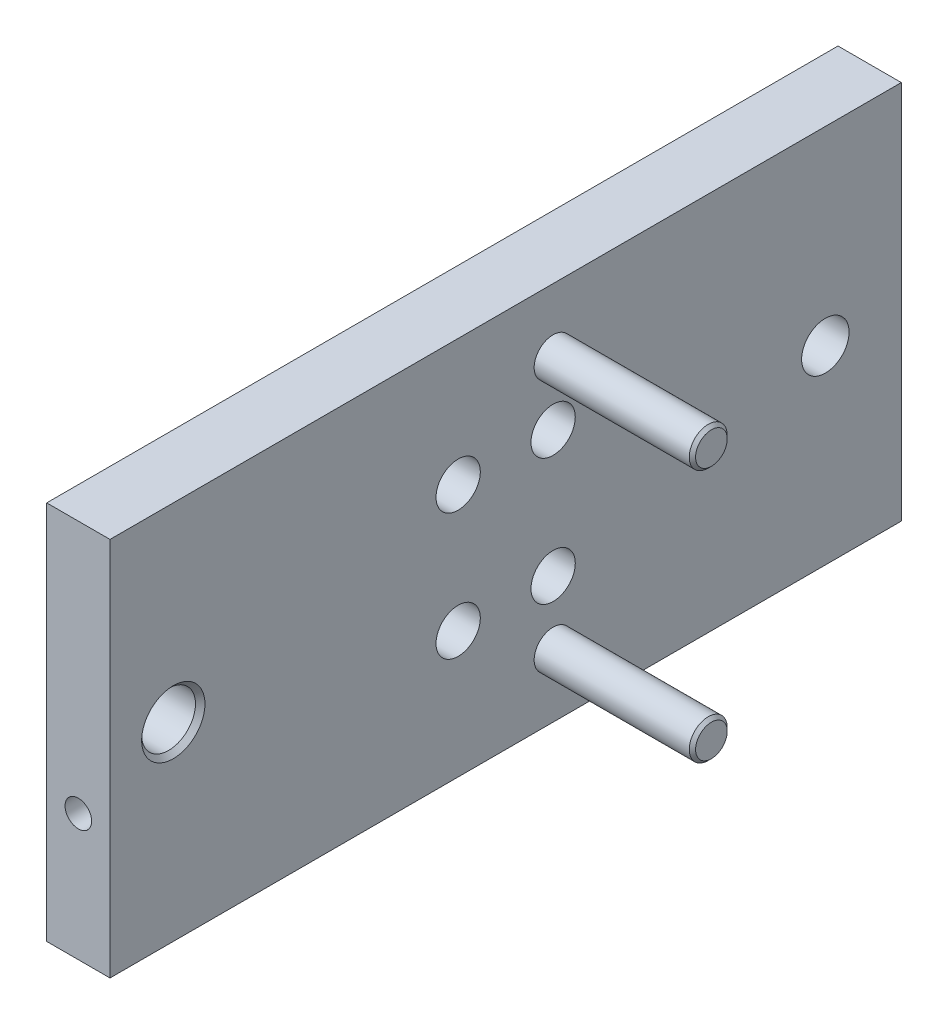
SolidWorks part; units mm, degrees
ref_plane "Front" through (0, 0, 0) normal (0, 0, 1) x (1, 0, 0)
ref_plane "Top" through (0, 0, 0) normal (0, 1, 0) x (1, 0, 0)
ref_plane "Right" through (0, 0, 0) normal (1, 0, 0) x (0, 0, -1)
sketch "Sketch1" plane through (0, 0, 0) normal (1, 0, 0) x (0, 0, -1)
  line L1 (0, 0) -> (-125, 0)
  line L2 (0, 0) -> (0, 60)
  line L3 (0, 60) -> (-125, 60)
  line L4 (-125, 0) -> (-125, 60)
  dimension "D1" = 60
  dimension "D2" = 125
extrude "Boss-Extrude1" add sketch "Sketch1" along normal blind 10
sketch "Sketch12" plane through (10, 0, 0) normal (1, 0, 0) x (0, 0, -1)
  line L0 (0, 30) -> (-125, 30) construction
  line L1 (0, 0) -> (0, 60) construction
  line L2 (-125, 60) -> (-125, 0) construction
  circle A0 centre (-55, 10) radius 3
  circle A1 centre (-55, 50) radius 3
  dimension "D1" = 6
  dimension "D2" = 55
  dimension "D3" = 40
extrude "Boss-Extrude2" add sketch "Sketch12" along normal blind 25
cosmetic thread "Cosmetic Thread3" parameters "D1"=10, "D2"=4.891
cosmetic thread "Cosmetic Thread4" parameters "D1"=10, "D2"=4.891
hole_wizard "M10 Tapped Hole1" positions "Sketch6" profile "Sketch5" tap size "M10" standard "ISO"
sketch "Sketch6" plane through (10, 0, 0) normal (1, 0, 0) x (0, 0, -1)
  line L0 (0, 30) -> (-125, 30) construction
  line L1 (0, 0) -> (0, 60) construction
  line L2 (-125, 60) -> (-125, 0) construction
  point P0 (-115, 30)
  dimension "D1" = 115
sketch "Sketch5" plane through (10, 30, 115) normal (0, 1, 0) x (0, 0, -1)
  line L0 (0, 0) -> (0, 27.0537)
  line L1 (0, 27.0537) -> (4.25, 24.5)
  line L2 (4.25, 24.5) -> (4.25, 0.75)
  line L3 (4.25, 0.75) -> (5, 0)
  line L5 (5, 0) -> (0, 0)
  line L6 (-4.25, 0.75) -> (-5, 0) construction
  line L10 (0, 27.0537) -> (-4.25, 24.5) construction
  line L11 (0, -6.35) -> (0, 107.95) construction
  dimension "Tap Drill Dia." = 8.5
  dimension "Tap Drill Depth" = 24.5
  dimension "Near C'Sink Dia." = 10
  dimension "Near C'Sink Angle" = 90
  dimension "Drill Angle" = 118
cosmetic thread "Hole Thread3" parameters "D1"=10, "D2"=10
sketch "Sketch7" plane through (10, 0, 0) normal (1, 0, 0) x (0, 0, -1)
  line L0 (0, 0) -> (0, 60) construction
  line L1 (0, 30) -> (-125, 30) construction
  line L2 (-125, 60) -> (-125, 0) construction
  circle A0 centre (-12, 30) radius 3.75
  dimension "D1" = 7.5
  dimension "D2" = 12
extrude "Cut-Extrude1" cut sketch "Sketch7" against normal through all
hole_wizard "CBORE for M3 Hex Socket Head Cap Screw1" positions "Sketch9" profile "Sketch8" counterbore size "M3" standard "ISO" end condition through all
sketch "Sketch9" plane through (10, 0, 0) normal (1, 0, 0) x (0, 0, -1)
  line L0 (0, 30) -> (-125, 30) construction
  line L1 (0, 0) -> (0, 60) construction
  line L2 (-125, 60) -> (-125, 0) construction
  point P0 (-70, 20)
  point P1 (-55, 20)
  point P3 (-55, 40)
  point P5 (-70, 40)
  dimension "D1" = 55
  dimension "D2" = 20
  dimension "D3" = 15
sketch "Sketch8" plane through (10, 20, 70) normal (0, 1, 0) x (0, 0, -1)
  line L0 (0, 0) -> (0, 10)
  line L1 (0, 10) -> (1.7, 10)
  line L3 (1.7, 10) -> (1.7, 5)
  line L4 (1.7, 5) -> (3.5, 5)
  line L5 (3.5, 5) -> (3.5, 0)
  line L7 (3.5, 0) -> (0, 0)
  line L11 (0, -6.35) -> (0, 107.95) construction
  dimension "Thru Hole Dia." = 3.4
  dimension "Thru Hole Depth" = 10
  dimension "C'Bore Dia." = 7
  dimension "C'Bore Depth" = 5
hole_wizard "M5 Tapped Hole1" positions "Sketch11" profile "Sketch10" tap size "M5" standard "ISO"
sketch "Sketch11" plane through (0, 0, 125) normal (0, 0, 1) x (1, 0, 0)
  line L0 (0, 60) -> (0, 0) construction
  line L1 (10, 0) -> (0, 0) construction
  point P0 (5, 20)
  dimension "D1" = 5
  dimension "D2" = 20
sketch "Sketch10" plane through (5, 20, 125) normal (1, 0, 0) x (0, -1, 0)
  line L0 (0, 0) -> (0, 13.6618)
  line L1 (0, 13.6618) -> (2.1, 12.4)
  line L2 (2.1, 12.4) -> (2.1, 0)
  line L5 (2.1, 0) -> (0, 0)
  line L10 (0, 13.6618) -> (-2.1, 12.4) construction
  line L11 (0, -6.35) -> (0, 107.95) construction
  dimension "Tap Drill Dia." = 4.2
  dimension "Tap Drill Depth" = 12.4
  dimension "Drill Angle" = 118
cosmetic thread "Hole Thread4" parameters "D1"=10, "D2"=5
chamfer "Chamfer2" distance 0.5 angle 45 2 edges at (35, 50, 52) (35, 10, 52)
